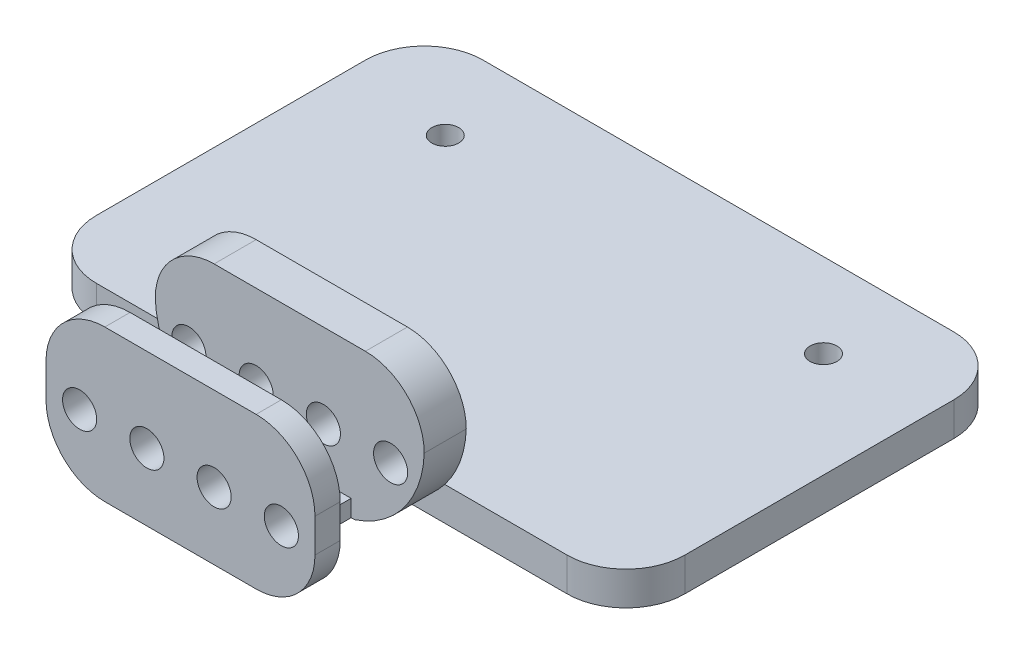
SolidWorks part; units mm, degrees
ref_plane "前视基准面" through (0, 0, 0) normal (0, 0, 1) x (1, 0, 0)
ref_plane "上视基准面" through (0, 0, 0) normal (0, 1, 0) x (1, 0, 0)
ref_plane "右视基准面" through (0, 0, 0) normal (1, 0, 0) x (0, 0, -1)
other "Configuration Table"
sketch "草图1" plane through (0, 0, 0) normal (0, 1, 0) x (1, 0, 0)
  line L1 (-35, 23) -> (35, 23)
  line L2 (-35, 23) -> (-35, -23)
  line L3 (-35, -23) -> (35, -23)
  line L4 (35, 23) -> (35, -23)
  line L5 (-35, 23) -> (35, -23) construction
  line L6 (-35, -23) -> (35, 23) construction
  point P0 (0, 0)
  dimension "D1" = 70
  dimension "D2" = 46
extrude "凸台-拉伸1" add sketch "草图1" along normal blind 4
sketch "草图2" plane through (0, 4, 0) normal (0, 1, 0) x (1, 0, 0)
  line L0 (-35, 13) -> (35, 13) construction
  line L1 (-35, 23) -> (-35, -23) construction
  line L2 (35, -23) -> (35, 23) construction
  line L4 (35, 23) -> (-35, 23) construction
  circle A0 centre (-22.5, 13) radius 1.6
  circle A1 centre (22.5, 13) radius 1.6
  point P8 (0, 13)
  point P9 (22.5, 13)
  point P10 (-22.5, 13)
  dimension "D1" = 10
  dimension "D2" = 22.5
  dimension "D3" = 22.5
extrude "切除-拉伸1" cut sketch "草图2" against normal up to next
sketch "草图3" plane through (0, 0, 23) normal (0, 0, 1) x (1, 0, 0)
  line L0 (-35, 0) -> (35, 0) construction
  line L1 (-16, 0) -> (16, 0)
  line L2 (-16, 0) -> (-16, 18)
  line L3 (16, 0) -> (16, 18)
  line L4 (-16, 18) -> (16, 18)
  point P0 (-16, 0)
  point P1 (16, 0)
  dimension "D1" = 16
  dimension "D2" = 16
extrude "凸台-拉伸2" add sketch "草图3" along normal blind 5
sketch "草图4" plane through (0, 0, 28) normal (0, 0, 1) x (1, 0, 0)
  line L0 (-16, 9) -> (16, 9) construction
  line L1 (-16, 18) -> (-16, 0) construction
  line L2 (16, 0) -> (16, 18) construction
  line L3 (-16, 1) -> (15.6044, 1) construction
  line L4 (-16, 0) -> (16, 0) construction
  line L5 (-7.6978, 2) -> (7.3022, 2)
  line L6 (-7.6978, 2) -> (-7.6978, 0)
  line L7 (-7.6978, 0) -> (7.3022, 0)
  line L8 (7.3022, 2) -> (7.3022, 0)
  line L9 (-7.6978, 2) -> (7.3022, 0) construction
  line L10 (-7.6978, 0) -> (7.3022, 2) construction
  point P8 (-0.1978, 1)
  dimension "D1" = 8
  dimension "D2" = 15
extrude "凸台-拉伸3" add sketch "草图4" along normal blind 10
sketch "草图5" plane through (0, 0, 38) normal (0, 0, 1) x (1, 0, 0)
  line L0 (-16, 0) -> (16, 0)
  line L1 (-16, 0) -> (-16, 18)
  line L2 (16, 0) -> (16, 18)
  line L3 (-16, 18) -> (16, 18)
  dimension "D1" = 18
extrude "凸台-拉伸4" add sketch "草图5" along normal blind 3
sketch "草图6" plane through (0, 0, 41) normal (0, 0, 1) x (1, 0, 0)
  line L0 (-20, 8) -> (20, 8) construction
  line L3 (-16, 0) -> (16, 0) construction
  circle A0 centre (-12, 8) radius 2.03
  circle A1 centre (-4, 8) radius 2.03
  circle A2 centre (4, 8) radius 2.03
  circle A3 centre (12, 8) radius 2.03
  point P6 (-12, 8)
  point P7 (-4, 8)
  point P8 (4, 8)
  point P9 (12, 8)
  point P10 (0, 8)
  dimension "D5" = 8
  dimension "D1" = 4
  dimension "D2" = 4
  dimension "D3" = 8
  dimension "D4" = 8
extrude "切除-拉伸2" cut sketch "草图6" against normal up to surface (18 mm away) up to face at (0, 11, 23)
sketch "草图8" plane through (0, 0, 23) normal (0, 0, -1) x (-1, 0, 0)
  line L0 (0, 0) -> (0, -12.5)
  line L1 (-35, 0) -> (35, 0) construction
  line L2 (0, -12.5) -> (27, -12.5)
  line L3 (0, -12.5) -> (-27, -12.5)
  dimension "D1" = 12.5
  dimension "D2" = 27
  dimension "D3" = 27
ref_plane "基准面1" through (0, -12.5, 0) normal (0, -1, 0) x (-1, 0, 0)
sketch "草图9" plane through (0, -12.5, 0) normal (0, -1, 0) x (-1, 0, 0)
  line L0 (27, -17) -> (27, -26.6611) construction
  line L1 (-27, -17) -> (-27, -21.8305) construction
fillet "圆角2" radius 7 10 edges at (16, 0, 39.5) (16, 18, 39.5) (-16, 18, 39.5) (-16, 0, 39.5) (16, 18, 25.5) (-16, 18, 25.5) (35, 2, 23) (35, 2, -23) (-35, 2, -23) (-35, 2, 23)
sketch "草图10" plane through (0, 0, 28) normal (0, 0, 1) x (1, 0, 0)
  line L0 (-16, 0) -> (-7.6978, 0) construction
  line L1 (-16, 11) -> (-16, 0)
  line L2 (-16, 0) -> (-7.6978, 0)
  line L3 (0, 0) -> (0, 14.1184) construction
  line L4 (16, 0) -> (7.6978, 0)
  line L5 (16, 11) -> (16, 0)
  arc A0 (-16, 11) -> (-7.6978, 0) centre (-4.0073, 11.4184) ccw
  arc A1 (16, 11) -> (7.6978, 0) centre (4.0073, 11.4184) cw
  point P0 (-16, 11)
  point P1 (-7.6978, 0)
extrude "切除-拉伸3" cut sketch "草图10" against normal up to surface (5 mm away) up to face at (-22, 2, 23)
